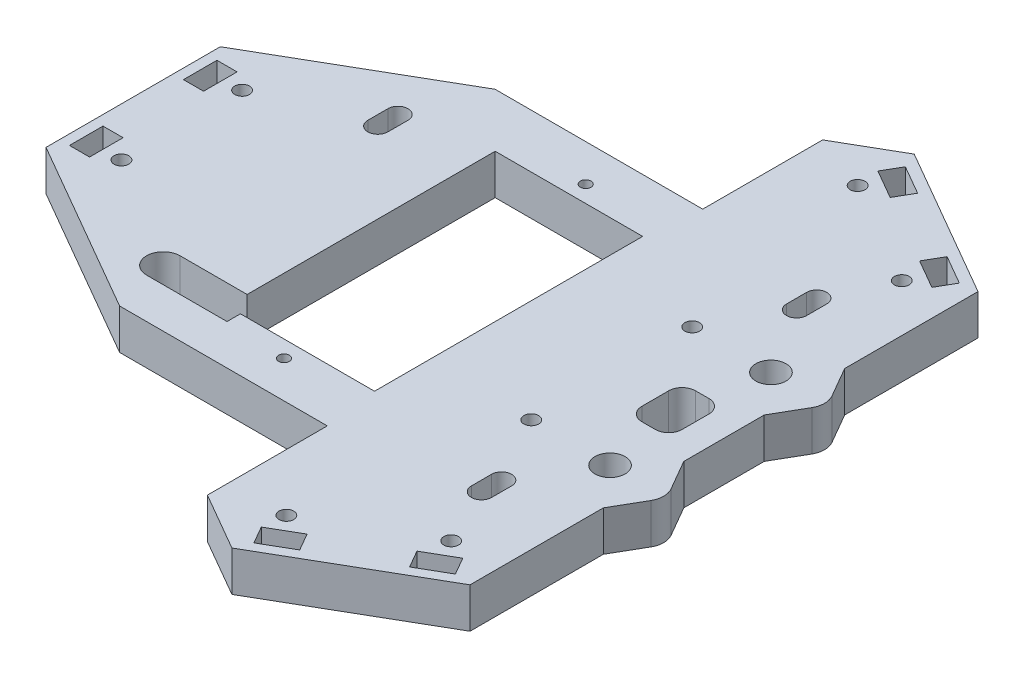
SolidWorks part; units mm, degrees
material "Acrylic (Medium-high impact)"
ref_plane "Front Plane" through (0, 0, 0) normal (0, 0, 1) x (1, 0, 0)
ref_plane "Top Plane" through (0, 0, 0) normal (0, 1, 0) x (1, 0, 0)
ref_plane "Right Plane" through (0, 0, 0) normal (1, 0, 0) x (0, 0, -1)
sketch "Sketch1" plane through (0, 0, 0) normal (0, 1, 0) x (1, 0, 0)
  line L0 (4.75, -20) -> (-15.25, -20)
  line L1 (-17.25, -17) -> (-17.25, 20)
  line L2 (-17.25, 20) -> (4.75, 20)
  line L3 (25.625, 44.3838) -> (22, 38.1051) construction
  line L4 (0, 0) -> (22, -38.1051) construction
  line L5 (0, 0) -> (-44, 0) construction
  line L6 (4.75, 20) -> (4.75, -20)
  line L7 (14.3667, 50.8838) -> (36.8833, 37.8838)
  line L8 (31.8833, 12) -> (31.8833, -12) construction
  line L9 (14.2058, 42.6051) -> (29.7942, 33.6051) construction
  line L10 (29.7942, -33.6051) -> (14.2058, -42.6051) construction
  line L11 (-44, 9) -> (-44, -9) construction
  line L12 (22, 38.1051) -> (0, 0) construction
  line L13 (22, -38.1051) -> (25.625, -44.3838) construction
  line L14 (-44, 0) -> (-51.25, 0) construction
  line L15 (0, 0) -> (31.8833, 0) construction
  line L16 (36.8833, 37.8838) -> (36.8833, -37.8838)
  line L17 (36.8833, -37.8838) -> (14.3667, -50.8838)
  line L18 (30.0712, 40.0848) -> (34.4013, 37.5848)
  line L19 (34.4013, 37.5848) -> (32.9013, 34.9867)
  line L20 (32.9013, 34.9867) -> (28.5712, 37.4867)
  line L21 (28.5712, 37.4867) -> (30.0712, 40.0848)
  line L22 (-51.25, 13) -> (-51.25, -13)
  line L23 (14.3667, 50.8838) -> (5.7064, 45.8838)
  line L24 (14.3667, -50.8838) -> (5.7064, -45.8838)
  line L25 (5.7064, 45.8838) -> (5.7064, 28)
  line L26 (5.7064, 28) -> (-25.2692, 28)
  line L27 (-25.2692, 28) -> (-51.25, 13)
  line L28 (5.7064, -45.8838) -> (5.7064, -28)
  line L29 (5.7064, -28) -> (-25.2692, -28)
  line L30 (-25.2692, -28) -> (-51.25, -13)
  line L31 (15.3487, 48.5848) -> (13.8487, 45.9867)
  line L32 (13.8487, 45.9867) -> (18.1788, 43.4867)
  line L33 (19.6788, 46.0848) -> (15.3487, 48.5848)
  line L34 (18.1788, 43.4867) -> (19.6788, 46.0848)
  line L35 (18.9288, 44.7857) -> (29.3212, 38.7857) construction
  line L36 (34.4013, -37.5848) -> (32.9013, -34.9867)
  line L37 (30.0712, -40.0848) -> (34.4013, -37.5848)
  line L38 (28.5712, -37.4867) -> (30.0712, -40.0848)
  line L39 (32.9013, -34.9867) -> (28.5712, -37.4867)
  line L40 (18.1788, -43.4867) -> (19.6788, -46.0848)
  line L41 (19.6788, -46.0848) -> (15.3487, -48.5848)
  line L42 (13.8487, -45.9867) -> (18.1788, -43.4867)
  line L43 (15.3487, -48.5848) -> (13.8487, -45.9867)
  line L44 (-49.75, -11) -> (-46.75, -11)
  line L45 (-49.75, -6) -> (-49.75, -11)
  line L46 (-46.75, -6) -> (-49.75, -6)
  line L47 (-46.75, -11) -> (-46.75, -6)
  line L48 (-46.75, 6) -> (-49.75, 6)
  line L49 (-49.75, 6) -> (-49.75, 11)
  line L50 (-46.75, 11) -> (-46.75, 6)
  line L51 (-49.75, 11) -> (-46.75, 11)
  line L52 (0, 0) -> (28.5712, 37.4867) construction
  line L53 (-15.25, -20) -> (-15.25, -22)
  line L54 (-15.25, -22) -> (-27.25, -22)
  line L56 (-27.25, -17) -> (-17.25, -17)
  line L57 (-29.25, 14.5) -> (-29.25, 17.5) construction
  line L58 (-30.75, 14.5) -> (-30.75, 17.5)
  line L59 (-27.75, 14.5) -> (-27.75, 17.5)
  line L63 (25.7064, -25) -> (25.7064, -22) construction
  line L64 (24.2064, -25) -> (24.2064, -22)
  line L65 (27.2064, -25) -> (27.2064, -22)
  line L66 (25.7064, 22) -> (25.7064, 25) construction
  line L67 (24.2064, 22) -> (24.2064, 25)
  line L68 (27.2064, 22) -> (27.2064, 25)
  line L69 (25.7064, -23.5) -> (25.7064, 0) construction
  line L70 (25.7064, 0) -> (25.7064, 23.5) construction
  line L71 (26.6333, -4) -> (32.6333, -4)
  line L72 (26.6333, -4) -> (26.6333, 4)
  line L73 (26.6333, 4) -> (32.6333, 4)
  line L74 (32.6333, -4) -> (32.6333, 4)
  line L75 (26.6333, -4) -> (32.6333, 4) construction
  line L76 (26.6333, 4) -> (32.6333, -4) construction
  circle A0 centre (14.2058, 42.6051) radius 1.1
  circle A1 centre (29.7942, 33.6051) radius 1.1
  circle A2 centre (29.7942, -33.6051) radius 1.1
  circle A3 centre (14.2058, -42.6051) radius 1.1
  circle A4 centre (-44, 9) radius 1.1
  circle A5 centre (-44, -9) radius 1.1
  circle A7 centre (14.2058, 42.6051) radius 2.5 construction
  arc A10 (24.2064, 22) -> (27.2064, 22) centre (25.7064, 22) ccw
  arc A11 (27.2064, 25) -> (24.2064, 25) centre (25.7064, 25) ccw
  arc A12 (-30.75, 14.5) -> (-27.75, 14.5) centre (-29.25, 14.5) ccw
  arc A13 (-27.75, 17.5) -> (-30.75, 17.5) centre (-29.25, 17.5) ccw
  circle A14 centre (-29.25, 14.5) radius 1.5 construction
  circle A15 centre (-29.25, 17.5) radius 1.5 construction
  arc A17 (24.2064, -25) -> (27.2064, -25) centre (25.7064, -25) ccw
  arc A18 (27.2064, -22) -> (24.2064, -22) centre (25.7064, -22) ccw
  arc A19 (-27.25, -17) -> (-27.25, -22) centre (-27.25, -19.5) ccw
  point P4 (-18.25, 0)
  point P38 (25.7064, 23.5)
  point P82 (-29.25, 16)
  point P85 (0, 0)
  point P92 (4.75, 0)
  point P93 (0, 0)
  point P102 (25.7064, -23.5)
  point P114 (29.6333, 0)
  point P148 (0, 0)
  dimension "D2" = 2.2
  dimension "D9" = 26
  dimension "D11" = 44
  dimension "D12" = 5
  dimension "D13" = 34
  dimension "D10" = 56
  dimension "D19" = 5
  dimension "D14" = 1.5
  dimension "D25" = 16
  dimension "D1" = 18
  dimension "D3" = 7.25
  dimension "D4" = 120
  dimension "D5" = 40
  dimension "D6" = 22
  dimension "D15" = 10
  dimension "D16" = 5
  dimension "D17" = 3
  dimension "D18" = 12
  dimension "D20" = 1.5
  dimension "D22" = 51.25
  dimension "D26" = 22
  dimension "D27" = 2
  dimension "D28" = 3
  dimension "D29" = 5
  dimension "D30" = 12
  dimension "D31" = 4.5
  dimension "D32" = 20
  dimension "D33" = 8
  dimension "D34" = 6
  dimension "D35" = 7.25
  dimension "D21" = 3
extrude "Boss-Extrude1" add sketch "Sketch1" along normal blind 6
sketch "Sketch10" plane through (0, 0, 0) normal (0, -1, 0) x (1, 0, 0)
  line L0 (-6.25, 22.5) -> (-6.25, -22.5) construction
  line L1 (4.75, 20) -> (4.75, -20) construction
  line L2 (4.75, -20) -> (-17.25, -20) construction
  point P4 (4.75, 0)
  point P5 (-6.25, 0)
  point P8 (-6.25, -20)
  dimension "D1" = 45
hole_wizard "Ø1.6 (1.6) Diameter Hole3" positions "3DSketch1" profile "Sketch11" hole size "Ø1.6" standard "ISO" end condition through all
sketch3d "3DSketch1"
  point P0 (-6.25, 0, 22.5)
  point P3 (-6.25, 0, -22.5)
sketch "Sketch11" plane through (-6.25, 0, 22.5) normal (1, 0, 0) x (0, 0, -1)
  line L0 (0, 0) -> (0, 6)
  line L1 (0, 6) -> (0.8, 6)
  line L2 (0.8, 6) -> (0.8, 0)
  line L5 (0.8, 0) -> (0, 0)
  line L11 (0, -6.35) -> (0, 107.95) construction
  dimension "Thru Hole Dia." = 1.6
  dimension "Thru Hole Depth" = 6
sketch "Sketch9" plane through (0, 0, 0) normal (0, -1, 0) x (1, 0, 0)
  line L0 (33.0083, -12) -> (30.7583, -12) construction
  line L1 (36.8833, 37.8838) -> (36.8833, -37.8838) construction
  line L2 (39.4814, 13.5) -> (36.8833, 18)
  line L3 (39.4814, 10.5) -> (36.8833, 6)
  line L4 (33.0083, 12) -> (30.7583, 12) construction
  line L5 (36.8833, 0) -> (0, 0) construction
  line L6 (36.8833, -18) -> (36.8833, -6)
  line L7 (39.4814, -10.5) -> (36.8833, -6)
  line L8 (39.4814, -13.5) -> (36.8833, -18)
  line L12 (36.8833, 18) -> (36.8833, 6)
  arc A0 (36.8833, 9) -> (36.8833, 15) centre (36.8833, 12) ccw
  arc A3 (36.8833, -9) -> (36.8833, -15) centre (36.8833, -12) cw
  dimension "D1" = 6
  dimension "D2" = 6
  dimension "D3" = 6
extrude "Boss-Extrude2" add sketch "Sketch9" against normal up to surface (6 mm away) contours A3 L6 | L6 A3 L7 | L8 A3 L6 | L12 A0 | A0 L12 L3 | A0 L2 L12 up to face at (-6.25, 6, 21.7)
fillet "Fillet1" radius 2 4 edges at (26.6333, 3, -4) (26.6333, 3, 4) (32.6333, 3, 4) (32.6333, 3, -4)
sketch "Sketch13" plane through (0, 6, 0) normal (0, 1, 0) x (1, 0, 0)
  line L0 (20.1333, 12) -> (20.1333, -12) construction
  line L1 (20.1333, 0) -> (34.6333, 0) construction
  line L2 (26.6333, 2) -> (26.6333, -2) construction
  line L3 (36.8833, -6) -> (36.8833, 6) construction
  line L4 (39.8833, 12) -> (31.8833, 12) construction
  line L5 (39.8833, -12) -> (31.8833, -12) construction
  arc A1 (39.4814, 10.5) -> (39.4814, 13.5) centre (36.8833, 12) ccw construction
  point P7 (26.6333, 0)
  dimension "D1" = 24
  dimension "D2" = 2.25
  dimension "D3" = 14.5
  dimension "D4" = 8
hole_wizard "Ø2.2 (2.2) Diameter Hole1" positions "3DSketch2" profile "Sketch14" hole size "Ø2.2" standard "ISO" end condition through all
sketch3d "3DSketch2"
  point P0 (20.1333, 6, -12)
  point P6 (20.1333, 6, 12)
sketch "Sketch14" plane through (20.1333, 6, -12) normal (1, 0, 0) x (0, 0, 1)
  line L0 (0, 0) -> (0, 6)
  line L1 (0, 6) -> (1.1, 6)
  line L2 (1.1, 6) -> (1.1, 0)
  line L5 (1.1, 0) -> (0, 0)
  line L11 (0, -6.35) -> (0, 107.95) construction
  dimension "Thru Hole Dia." = 2.2
  dimension "Thru Hole Depth" = 6
hole_wizard "Ø4.0mm Dowel Hole1" positions "3DSketch3" profile "Sketch15" hole size "Ø4.0" standard "ANSI Metric" end condition through all
sketch3d "3DSketch3"
  point P0 (31.8833, 6, -12)
  point P3 (31.8833, 6, 12)
sketch "Sketch15" plane through (31.8833, 6, -12) normal (1, 0, 0) x (0, 0, 1)
  line L0 (0, 0) -> (0, 6)
  line L1 (0, 6) -> (2.25, 6)
  line L2 (2.25, 6) -> (2.25, 0)
  line L5 (2.25, 0) -> (0, 0)
  line L11 (0, -6.35) -> (0, 107.95) construction
  dimension "Thru Hole Dia." = 4.5
  dimension "Thru Hole Depth" = 6
